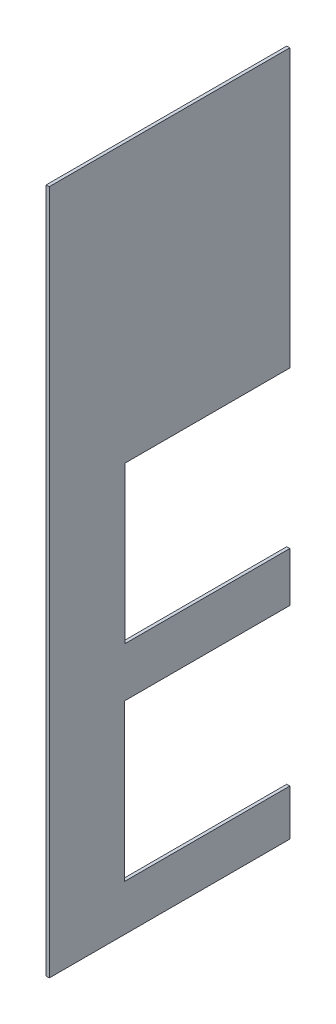
SolidWorks part; units mm, degrees
ref_plane "Спереди" through (0, 0, 0) normal (0, 0, 1) x (1, 0, 0)
ref_plane "Сверху" through (0, 0, 0) normal (0, 1, 0) x (1, 0, 0)
ref_plane "Справа" through (0, 0, 0) normal (1, 0, 0) x (0, 0, -1)
ref_plane "Плоскость4" through (0.5, 0, 0) normal (-1, 0, 0) x (0, -1, 0)
sketch "Эскиз1" plane through (0.5, 0, 0) normal (-1, 0, 0) x (0, -1, 0)
  line L0 (9.85, 42.25) -> (-100.85, 42.25)
  line L1 (-100.85, 42.25) -> (-100.85, 3.4)
  line L2 (-100.85, 3.4) -> (9.85, 3.4)
  line L3 (9.85, 3.4) -> (9.85, 42.25)
extrude "Бобышка-Вытянуть1" add sketch "Эскиз1" against normal blind 0.5
sketch "Эскиз3" plane through (0.5, 0, 0) normal (-1, 0, 0) x (0, 0, 1)
  line L0 (6.9066, -1.9179) -> (29.5066, -1.9179) construction
  line L1 (30.0066, 30.8071) -> (-3.688, 30.8071)
  line L2 (30.0066, 30.8071) -> (30.0066, 56.0571)
  line L3 (30.0066, 56.0571) -> (-3.688, 56.0571)
  line L4 (-3.688, 30.8071) -> (-3.688, 56.0571)
  line L5 (29.5066, 39.8221) -> (29.5066, 43.2321) construction
  line L6 (29.5066, 55.5571) -> (6.9066, 55.5571) construction
  line L7 (6.9066, 31.3071) -> (29.5066, 31.3071) construction
  line L8 (30.1066, -2.4179) -> (-3.688, -2.4179)
  line L9 (30.1066, -2.4179) -> (30.1066, 22.8321)
  line L10 (30.1066, 22.8321) -> (-3.688, 22.8321)
  line L11 (-3.688, -2.4179) -> (-3.688, 22.8321)
  line L12 (29.5066, 22.3321) -> (6.9066, 22.3321) construction
  line L13 (29.6066, 10.4071) -> (29.6066, 13.8171) construction
  dimension "D1" = 0.5
  dimension "D2" = 0.5
  dimension "D3" = 0.5
  dimension "D4" = 0.5
  dimension "D5" = 0.5
  dimension "D6" = 0.5
extrude "Вырез-Вытянуть1" cut sketch "Эскиз3" against normal through all
